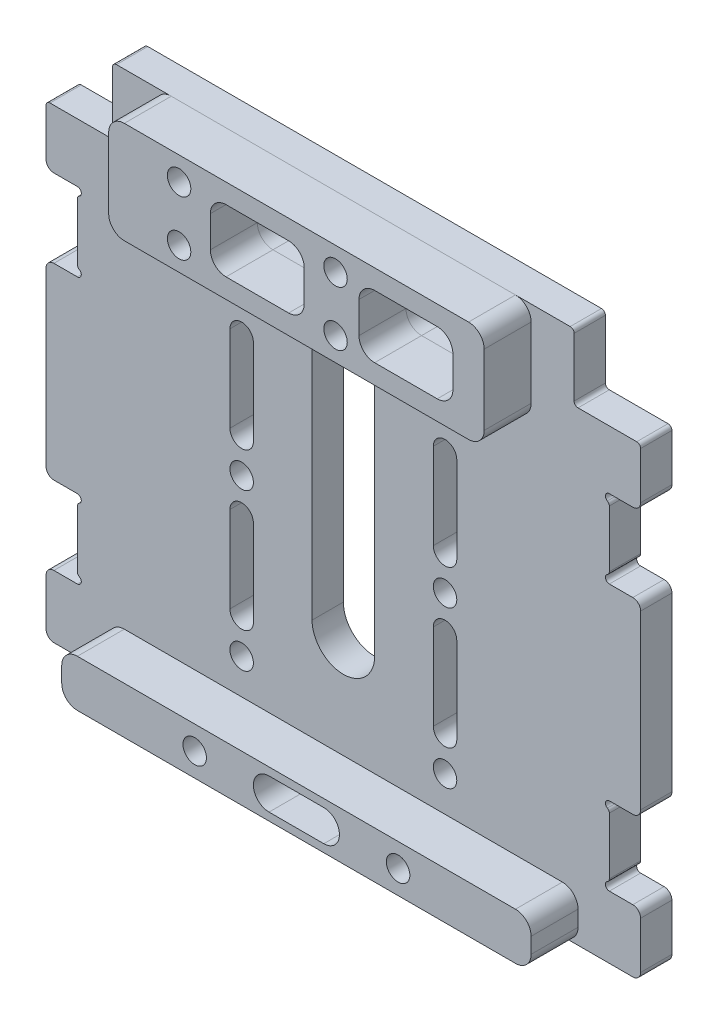
SolidWorks part; units mm, degrees
material "Thornel Mat VMA"
ref_plane "前视基准面" through (0, 0, 0) normal (0, 0, 1) x (1, 0, 0)
ref_plane "上视基准面" through (0, 0, 0) normal (0, 1, 0) x (1, 0, 0)
ref_plane "右视基准面" through (0, 0, 0) normal (1, 0, 0) x (0, 0, -1)
other "Configuration Table"
sketch "草图1" plane through (0, 0, 0) normal (0, 0, 1) x (1, 0, 0)
  line L0 (0, 0) -> (0, -16.7231) construction
  line L1 (-38, -34) -> (38, -34)
  line L2 (-38, -34) -> (-38, 34)
  line L3 (-38, 34) -> (38, 34)
  line L4 (38, -34) -> (38, 34)
  line L5 (-38, -34) -> (38, 34) construction
  line L6 (-38, 34) -> (38, -34)
  line L7 (-34, 18) -> (-38, 8) construction
  line L8 (34, -26) -> (38, -26)
  line L9 (34, -26) -> (34, -16)
  line L10 (34, -16) -> (38, -16)
  line L11 (38, -26) -> (38, -16)
  line L12 (34, -26) -> (38, -16) construction
  line L13 (34, -16) -> (38, -26) construction
  line L14 (34, 8) -> (38, 8)
  line L15 (34, 8) -> (34, 18)
  line L16 (34, 18) -> (38, 18)
  line L17 (38, 8) -> (38, 18)
  line L18 (34, 8) -> (38, 18) construction
  line L19 (34, 18) -> (38, 8) construction
  line L20 (-34, 8) -> (-38, 18) construction
  line L21 (-34, -16) -> (-38, -26) construction
  line L22 (-34, -26) -> (-38, -16) construction
  line L23 (-38, 8) -> (-38, 18)
  line L24 (-34, 18) -> (-38, 18)
  line L25 (-34, 8) -> (-34, 18)
  line L26 (-34, 8) -> (-38, 8)
  line L27 (-38, -26) -> (-38, -16)
  line L28 (-34, -16) -> (-38, -16)
  line L29 (-34, -26) -> (-34, -16)
  line L30 (-34, -26) -> (-38, -26)
  point P0 (0, 0)
  point P8 (36, -21)
  point P13 (36, 13)
  point P26 (-36, 13)
  point P27 (-36, -21)
  dimension "D1" = 76
  dimension "D2" = 68
  dimension "D3" = 8
  dimension "D4" = 10
  dimension "D5" = 42
  dimension "D6" = 4
extrude "凸台-拉伸1" add sketch "草图1" along normal blind 4 contours L29 L30 L2 L1 L6 L24 L25 L26 L28 | L15 L16 L4 L3 L6 L8 L9 L10 L14
sketch "草图3" plane through (0, 0, 4) normal (0, 0, 1) x (1, 0, 0)
  line L0 (0, 0) -> (0, 19.8794) construction
  line L1 (13, 16.5) -> (13, -3.5) construction
  line L2 (13, -3.5) -> (13, -23.5) construction
  line L3 (-38, -34) -> (38, -34) construction
  line L4 (-13, -3.5) -> (-13, -23.5) construction
  line L5 (-13, 16.5) -> (-13, -3.5) construction
  circle A0 centre (13, 16.5) radius 1.5
  circle A1 centre (13, -3.5) radius 1.5
  circle A2 centre (13, -23.5) radius 1.5
  circle A3 centre (-13, -23.5) radius 1.5
  circle A4 centre (-13, -3.5) radius 1.5
  circle A5 centre (-13, 16.5) radius 1.5
  dimension "D2" = 3
  dimension "D4" = 10.5
  dimension "D1" = 20
  dimension "D3" = 13
extrude "切除-拉伸2" cut sketch "草图3" against normal up to surface (4 mm away) up to face at (0, -3.2, 0)
sketch "草图4" plane through (0, 0, 4) normal (0, 0, 1) x (1, 0, 0)
  line L0 (0, 0) -> (0, 27.5) construction
  line L1 (-38, 34) -> (38, 34) construction
  line L2 (-24, 21) -> (24, 21)
  line L3 (-24, 21) -> (-24, 34)
  line L4 (-24, 34) -> (24, 34)
  line L5 (24, 21) -> (24, 34)
  line L6 (-24, 21) -> (24, 34) construction
  line L7 (-24, 34) -> (24, 21) construction
  dimension "D1" = 13
  dimension "D2" = 48
extrude "凸台-拉伸2" add sketch "草图4" along normal blind 6 separate body
sketch "草图5" plane through (0, 0, 10) normal (0, 0, 1) x (1, 0, 0)
  line L0 (38, 18) -> (38, 34) construction
  line L1 (-15, 24) -> (5, 24) construction
  line L2 (-15, 24) -> (-15, 31) construction
  line L3 (-15, 31) -> (5, 31) construction
  line L4 (5, 24) -> (5, 31) construction
  line L5 (-15, 24) -> (5, 31) construction
  line L6 (-15, 31) -> (5, 24) construction
  line L8 (24, 34) -> (-24, 34) construction
  circle A0 centre (5, 31) radius 1.5
  circle A1 centre (5, 24) radius 1.5
  circle A2 centre (-15, 24) radius 1.5
  circle A3 centre (-15, 31) radius 1.5
  point P0 (-5, 27.5)
  dimension "D5" = 3
  dimension "D1" = 33
  dimension "D2" = 20
  dimension "D3" = 3
  dimension "D4" = 7
extrude "切除-拉伸3" cut sketch "草图5" against normal up to surface (10 mm away)
sketch "草图6" plane through (0, 0, 4) normal (0, 0, 1) x (1, 0, 0)
  line L0 (-13, -23.5) -> (-13, -34) construction
  line L1 (-38, -34) -> (38, -34) construction
  line L2 (0, 0) -> (0, -43.728) construction
  line L4 (-30, -28) -> (30, -28)
  line L5 (-30, -28) -> (-30, -34)
  line L6 (-30, -34) -> (30, -34)
  line L7 (30, -28) -> (30, -34)
  line L8 (-30, -28) -> (30, -34) construction
  line L9 (-30, -34) -> (30, -28) construction
  point P5 (0, -31)
  dimension "D1" = 6
  dimension "D2" = 60
extrude "凸台-拉伸3" add sketch "草图6" along normal blind 6 separate body
sketch "草图7" plane through (0, 0, 10) normal (0, 0, 1) x (1, 0, 0)
  line L0 (-30, -31) -> (-13, -31) construction
  line L1 (-30, -28) -> (-30, -34) construction
  line L2 (-13, -23.5) -> (-13, -31) construction
  line L3 (0, 0) -> (0, -41.9101) construction
  line L4 (13, -23.5) -> (13, -31) construction
  line L5 (30, -31) -> (13, -31) construction
  line L6 (-13, -31) -> (-3, -31) construction
  circle A0 centre (-13, -31) radius 1.5
  circle A1 centre (13, -31) radius 1.5
  circle A2 centre (-3, -31) radius 1.5
  circle A3 centre (3, -31) radius 1.5
  dimension "D1" = 3
  dimension "D2" = 10
extrude "切除-拉伸4" cut sketch "草图7" against normal up to surface (10 mm away)
sketch "草图8" plane through (0, 0, 10) normal (0, 0, 1) x (1, 0, 0)
  line L0 (-15, 31) -> (5, 24) construction
  line L1 (-5, 27.5) -> (14, 27.5) construction
  line L3 (-11, 23.5) -> (1, 23.5)
  line L4 (-11, 23.5) -> (-11, 31.5)
  line L5 (-11, 31.5) -> (1, 31.5)
  line L6 (1, 23.5) -> (1, 31.5)
  line L7 (-11, 23.5) -> (1, 31.5) construction
  line L8 (-11, 31.5) -> (1, 23.5) construction
  line L9 (8, 23.5) -> (20, 23.5)
  line L10 (8, 23.5) -> (8, 31.5)
  line L11 (8, 31.5) -> (20, 31.5)
  line L12 (20, 23.5) -> (20, 31.5)
  line L13 (8, 23.5) -> (20, 31.5) construction
  line L14 (8, 31.5) -> (20, 23.5) construction
  circle A0 centre (5, 31) radius 1.5 construction
  dimension "D1" = 8
  dimension "D2" = 12
  dimension "D3" = 12
  dimension "D4" = 3
extrude "切除-拉伸5" cut sketch "草图8" against normal up to surface (10 mm away)
sketch "草图9" plane through (0, 0, 10) normal (0, 0, 1) x (1, 0, 0)
  line L0 (-3, -31) -> (3, -31) construction
  line L1 (-3.5, -31) -> (3.5, -31) construction
  line L2 (-3.5, -29) -> (3.5, -29)
  line L3 (-3.5, -33) -> (3.5, -33)
  line L4 (0, -31) -> (0, 0) construction
  arc A0 (-3.5, -29) -> (-3.5, -33) centre (-3.5, -31) ccw
  arc A1 (3.5, -33) -> (3.5, -29) centre (3.5, -31) ccw
  point P6 (0, -31)
  dimension "D2" = 2
  dimension "D1" = 7
extrude "切除-拉伸6" cut sketch "草图9" against normal up to surface (10 mm away)
fillet "圆角1" radius 2 4 edges at (30, -34, 7) (-30, -34, 7) (-30, -28, 7) (30, -28, 7)
fillet "圆角2" radius 2 12 edges at (20, 23.5, 7) (8, 31.5, 7) (20, 31.5, 7) (1, 23.5, 7) (-11, 23.5, 7) (-11, 31.5, 7) (1, 31.5, 7) (8, 23.5, 7) (24, 21, 7) (-24, 21, 7) (-24, 34, 7) (24, 34, 7)
sketch "草图10" plane through (0, 0, 4) normal (0, 0, 1) x (1, 0, 0)
  line L0 (0, 0) -> (0, 41.9559) construction
  line L1 (-34, 8) -> (-34, 18) construction
  line L2 (-34, -26) -> (-34, -16) construction
  line L3 (-34, -26) -> (-38, -26) construction
  line L4 (-34, -26) -> (-34, 18)
  line L5 (34, -26) -> (34, 18)
  arc A0 (-34, 18) -> (-34, 17) centre (-34, 17.5) cw
  arc A1 (-34, 8) -> (-34, 9) centre (-34, 8.5) ccw
  arc A2 (-34, -16) -> (-34, -17) centre (-34, -16.5) cw
  arc A3 (-34, -26) -> (-34, -25) centre (-34, -25.5) ccw
  arc A4 (34, -26) -> (34, -25) centre (34, -25.5) cw
  arc A5 (34, -16) -> (34, -17) centre (34, -16.5) ccw
  arc A6 (34, 8) -> (34, 9) centre (34, 8.5) cw
  arc A7 (34, 18) -> (34, 17) centre (34, 17.5) ccw
  line M27 (-34, -16) -> (-34, -26)
  line M33 (34, -26) -> (34, -16)
  line M37 (34, 8) -> (34, 18)
  line M43 (-34, 18) -> (-34, 8)
  dimension "D1" = 0.5
extrude "切除-拉伸7" cut sketch "草图10" against normal up to surface (4 mm away) contours A4 M33 | A5 M33 | A6 M37 | A7 M37 | A0 M43 | A1 M43 | A3 M27 | A2 M27 up to face at (0, -31, 0)
sketch "草图11" plane through (0, 0, 4) normal (0, 0, 1) x (1, 0, 0)
  line L0 (0, 0) -> (0, -52.0396) construction
  line L1 (-13, 16.5) -> (-13, -3.5) construction
  line L2 (-13, -3.5) -> (-13, -23.5) construction
  line L3 (-13, 12) -> (-13, 1) construction
  line L4 (-11.5, 12) -> (-11.5, 1)
  line L5 (-14.5, 12) -> (-14.5, 1)
  line L6 (-13, -3.5) -> (23.5947, -3.5) construction
  line L7 (-13, -19) -> (-13, -8) construction
  line L8 (-11.5, -19) -> (-11.5, -8)
  line L9 (-14.5, -19) -> (-14.5, -8)
  line L10 (13, -3.5) -> (13, -23.5) construction
  line L11 (13, 16.5) -> (13, -3.5) construction
  line L12 (13, -19) -> (13, -8) construction
  line L13 (11.5, -19) -> (11.5, -8)
  line L14 (14.5, -19) -> (14.5, -8)
  line L15 (13, 12) -> (13, 1) construction
  line L16 (11.5, 12) -> (11.5, 1)
  line L17 (14.5, 12) -> (14.5, 1)
  arc A0 (-11.5, 12) -> (-14.5, 12) centre (-13, 12) ccw
  arc A1 (-14.5, 1) -> (-11.5, 1) centre (-13, 1) ccw
  circle A2 centre (-13, 16.5) radius 1.5 construction
  circle A3 centre (-13, -3.5) radius 1.5 construction
  arc A4 (-11.5, -19) -> (-14.5, -19) centre (-13, -19) cw
  arc A5 (-14.5, -8) -> (-11.5, -8) centre (-13, -8) cw
  arc A6 (11.5, -19) -> (14.5, -19) centre (13, -19) ccw
  arc A7 (14.5, -8) -> (11.5, -8) centre (13, -8) ccw
  arc A8 (11.5, 12) -> (14.5, 12) centre (13, 12) cw
  arc A9 (14.5, 1) -> (11.5, 1) centre (13, 1) cw
  point P11 (-13, 6.5)
  point P23 (-13, -13.5)
  point P33 (13, -13.5)
  point P40 (13, 6.5)
  dimension "D1" = 1.5
  dimension "D2" = 4.5
  dimension "D3" = 4.5
extrude "切除-拉伸8" cut sketch "草图11" against normal up to surface (4 mm away) contours L5 A1 L4 A0 | A9 L17 A8 L16 | L14 A7 L13 A6 | A5 L9 A4 L8 up to face at (0, -31, 0)
sketch "草图12" plane through (0, 0, 4) normal (0, 0, 1) x (1, 0, 0)
  line L0 (0, 0) -> (0, 15) construction
  line L1 (0, 15) -> (0, -15) construction
  line L2 (4, 15) -> (4, -15)
  line L3 (-4, 15) -> (-4, -15)
  arc A0 (4, 15) -> (-4, 15) centre (0, 15) ccw
  arc A1 (-4, -15) -> (4, -15) centre (0, -15) ccw
  point P3 (0, 0)
  dimension "D1" = 4
  dimension "D2" = 30
  dimension "D3" = 15
extrude "切除-拉伸9" cut sketch "草图12" against normal up to surface (4 mm away) up to face at (13, 6.5, 0)
fillet "圆角3" radius 0.5 8 edges at (34, -25, 2) (34, -17, 2) (34, 9, 2) (34, 17, 2) (-34, -25, 2) (-34, -17, 2) (-34, 9, 2) (-34, 17, 2)
fillet "圆角4" radius 2 8 edges at (8, 23.5, 2) (8, 31.5, 2) (20, 31.5, 2) (20, 23.5, 2) (-11, 31.5, 2) (1, 31.5, 2) (1, 23.5, 2) (-11, 23.5, 2)
fillet "圆角5" radius 1 12 edges at (38, -26, 2) (38, -34, 2) (-38, -34, 2) (-38, -26, 2) (-38, -16, 2) (-38, 8, 2) (-38, 34, 2) (38, 34, 2) (38, 18, 2) (38, 8, 2) (38, -16, 2) (-38, 18, 2)
sketch "草图13" plane through (0, 0, 4) normal (0, 0, 1) x (1, 0, 0)
  line L0 (0, 0) -> (0, 46.4149) construction
  line L1 (-38, 19) -> (-38, 33) construction
  line L2 (-38, 25.5) -> (-29.5, 25.5)
  line L3 (-38, 25.5) -> (-38, 34)
  line L4 (-38, 34) -> (-29.5, 34)
  line L5 (-29.5, 25.5) -> (-29.5, 34)
  line L6 (-37, 34) -> (37, 34) construction
  line L7 (29.5, 25.5) -> (29.5, 34)
  line L8 (38, 34) -> (29.5, 34)
  line L9 (38, 25.5) -> (38, 34)
  line L10 (38, 25.5) -> (29.5, 25.5)
  dimension "D1" = 8.5
extrude "切除-拉伸10" cut sketch "草图13" against normal up to surface (4 mm away) up to face at (0, 0, 0)
fillet "圆角6" radius 0.5 6 edges at (-38, 25.5, 2) (29.5, 25.5, 2) (29.5, 34, 2) (-29.5, 34, 2) (-29.5, 25.5, 2) (38, 25.5, 2)
